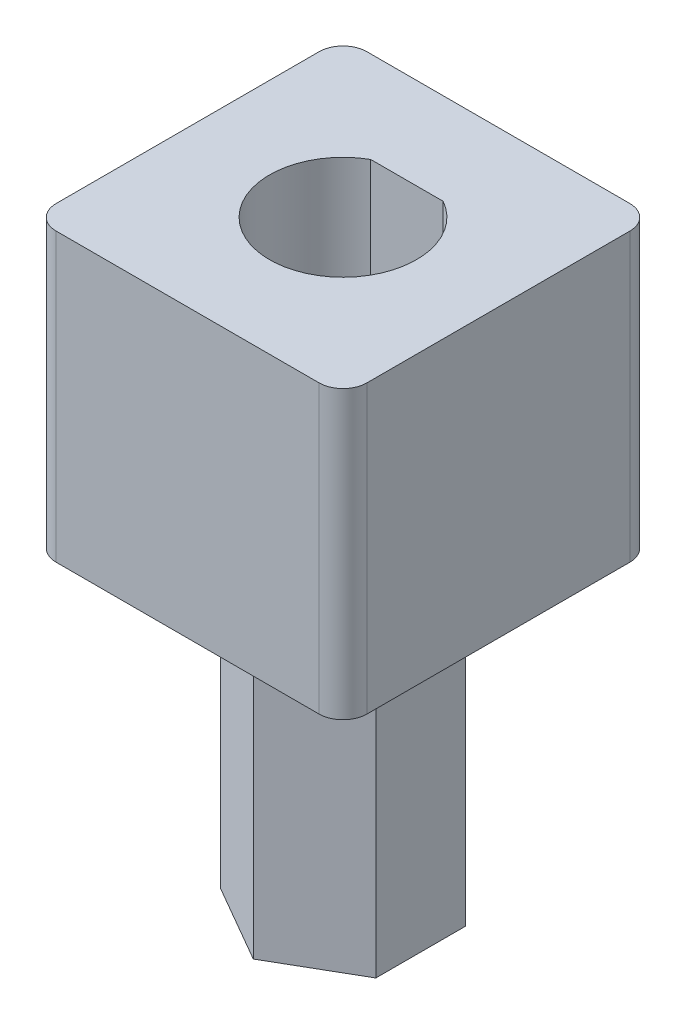
SolidWorks part; units mm, degrees
ref_plane "Front Plane" through (0, 0, 0) normal (0, 0, 1) x (1, 0, 0)
ref_plane "Top Plane" through (0, 0, 0) normal (0, 1, 0) x (1, 0, 0)
ref_plane "Right Plane" through (0, 0, 0) normal (1, 0, 0) x (0, 0, -1)
sketch "Sketch1" plane through (0, 0, 0) normal (0, 1, 0) x (1, 0, 0)
  line L1 (0, -3.7528) -> (3.25, -1.8764)
  line L2 (3.25, -1.8764) -> (3.25, 1.8764)
  line L3 (3.25, 1.8764) -> (0, 3.7528)
  line L4 (0, 3.7528) -> (-3.25, 1.8764)
  line L5 (-3.25, 1.8764) -> (-3.25, -1.8764)
  line L6 (-3.25, -1.8764) -> (0, -3.7528)
  circle A0 centre (0, 0) radius 3.25 construction
  circle A1 centre (0, 0) radius 1.425
  point P10 (-3.2377, -1.8976)
  point P11 (0, 0)
  dimension "D2" = 2.85
  dimension "D1" = 6.5
extrude "Boss-Extrude1" add sketch "Sketch1" along normal blind 13
sketch "Sketch2" plane through (0, 13, 0) normal (0, 1, 0) x (1, 0, 0)
  line L1 (-6.5, 6.5) -> (6.5, 6.5)
  line L2 (-6.5, 6.5) -> (-6.5, -6.5)
  line L3 (-6.5, -6.5) -> (6.5, -6.5)
  line L4 (6.5, 6.5) -> (6.5, -6.5)
  circle A0 centre (0, 0) radius 3.075
  point P3 (0, 0)
  point P8 (-6.5, 0)
  point P9 (0, -6.5)
  dimension "D1" = 6.15
  dimension "D2" = 6.5
  dimension "D3" = 6.5
extrude "Boss-Extrude2" add sketch "Sketch2" along normal blind 12
sketch "Sketch3" plane through (0, 25, 0) normal (0, 1, 0) x (1, 0, 0)
  line L0 (-1.5166, 2.675) -> (1.5166, 2.675)
  circle A0 centre (0, 0) radius 3.075 construction
  arc A2 (1.5166, 2.675) -> (-1.5166, 2.675) centre (0, 0) ccw
  circle A3 centre (0, 0) radius 3.075 construction
  point P6 (0, 3.075)
  dimension "D1" = 0.4
extrude "Boss-Extrude3" add sketch "Sketch3" against normal up to next
sketch "Sketch5" plane through (0, 0, -2.675) normal (0, 0, 1) x (1, 0, 0)
  circle A0 centre (0, 20) radius 1.425
  point P3 (0, 0)
  dimension "D1" = 2.85
  dimension "D2" = 20
extrude "Cut-Extrude1" cut sketch "Sketch5" against normal blind 12
fillet "Fillet2" radius 1 4 edges at (6.5, 19, 6.5) (-6.5, 19, 6.5) (6.5, 19, -6.5) (-6.5, 19, -6.5)
sketch "Sketch8" plane through (0, 0, 0) normal (1, 0, 0) x (0, 0, -1)
  line L0 (0, -1000) -> (0, 49000) construction
  line L1 (0, 13) -> (-3.7528, 13)
  line L2 (-3.7528, 13) -> (-6.2528, 13)
  line L3 (-6.2528, 13) -> (-3.7528, 11)
  line L4 (-3.7528, 11) -> (0, 11)
  line L5 (0, 11) -> (0, 13)
  line L6 (-6.5, 13) -> (-5.5, 13) construction
  line L7 (-3.7528, 13) -> (-3.7528, 0) construction
  point P5 (0, 10.4377)
  point P11 (-5.799, 13)
  point P12 (0, 0)
  dimension "D1" = 2
  dimension "D2" = 2.5
revolve "Revolve1" add sketch "Sketch8" angle 360 about L0
